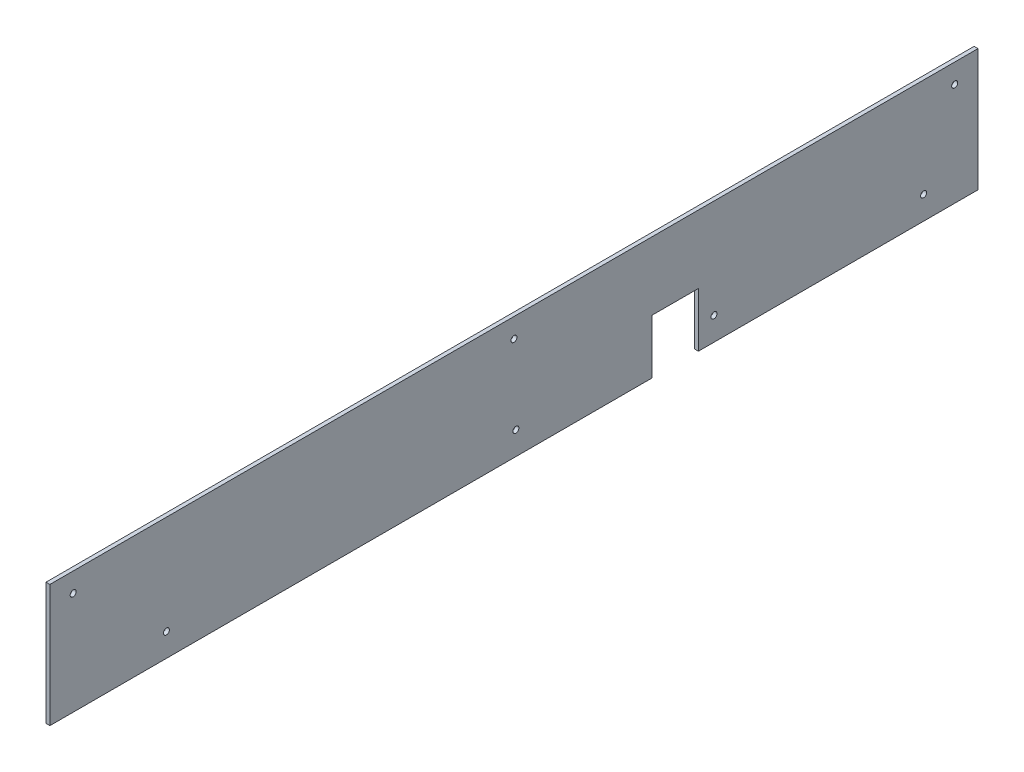
SolidWorks part; units mm, degrees
material "ABS PC"
ref_plane "Front Plane" through (0, 0, 0) normal (0, 0, 1) x (1, 0, 0)
ref_plane "Top Plane" through (0, 0, 0) normal (0, 1, 0) x (1, 0, 0)
ref_plane "Right Plane" through (0, 0, 0) normal (1, 0, 0) x (0, 0, -1)
sketch "Sketch2" plane through (0, 0, 0) normal (1, 0, 0) x (0, 0, -1)
  line L1 (0, 0) -> (758.825, 0)
  line L2 (0, 0) -> (0, 100.0125)
  line L3 (0, 100.0125) -> (758.825, 100.0125)
  line L4 (758.825, 0) -> (758.825, 100.0125)
  dimension "D1" = 100.0125
  dimension "D2" = 758.825
extrude "Boss-Extrude1" add sketch "Sketch2" along normal blind 3.175
hole_wizard "#10 (0.1935) Diameter Hole2" positions "Sketch5" profile "Sketch6" hole size "#10" standard "ANSI Inch" end condition through all
sketch "Sketch5" plane through (3.175, 0, 0) normal (1, 0, 0) x (0, 0, -1)
  line L0 (379.4125, 100.0125) -> (379.4125, 0) construction
  line L1 (758.825, 100.0125) -> (0, 100.0125) construction
  line L2 (0, 0) -> (758.825, 0) construction
  line L4 (0, 100.0125) -> (0, 0) construction
  line L5 (758.825, 0) -> (758.825, 100.0125) construction
  line L6 (0, 100.0125) -> (0, 0) construction
  line L7 (381, 19.05) -> (95.25, 19.05) construction
  line L9 (0, 0) -> (758.825, 0) construction
  point P0 (19.05, 84.1375)
  point P2 (379.4125, 84.1375)
  point P4 (739.775, 84.1375)
  point P20 (95.25, 19.05)
  point P22 (381, 19.05)
  point P33 (542.9885, 19.05)
  point P35 (714.375, 19.05)
  dimension "D1" = 0
  dimension "D2" = 19.05
  dimension "D3" = 15.875
  dimension "D4" = 15.875
  dimension "D5" = 15.875
  dimension "D6" = 19.05
  dimension "D7" = 95.25
  dimension "D8" = 285.75
  dimension "D9" = 19.05
  dimension "D10" = 44.45
  dimension "D11" = 19.05
  dimension "D12" = 171.3865
sketch "Sketch6" plane through (3.175, 84.1375, -19.05) normal (0, 1, 0) x (0, 0, -1)
  line L0 (0, 0) -> (0, 3.175)
  line L1 (0, 3.175) -> (2.4574, 3.175)
  line L2 (2.4574, 3.175) -> (2.4574, 0)
  line L5 (2.4574, 0) -> (0, 0)
  line L11 (0, -6.35) -> (0, 107.95) construction
  dimension "Thru Hole Dia." = 4.9149
  dimension "Thru Hole Depth" = 3.175
sketch "Sketch7" plane through (3.175, 0, 0) normal (1, 0, 0) x (0, 0, -1)
  line L0 (492.125, 0) -> (492.125, 44.45)
  line L1 (0, 0) -> (758.825, 0) construction
  line L2 (492.125, 44.45) -> (530.225, 44.45)
  line L3 (530.225, 44.45) -> (530.225, 0)
  line L4 (492.125, 0) -> (530.225, 0)
  circle A0 centre (381, 19.05) radius 2.4574 construction
  dimension "D1" = 38.1
  dimension "D2" = 111.125
  dimension "D3" = 44.45
extrude "Cut-Extrude3" cut sketch "Sketch7" against normal blind 254
